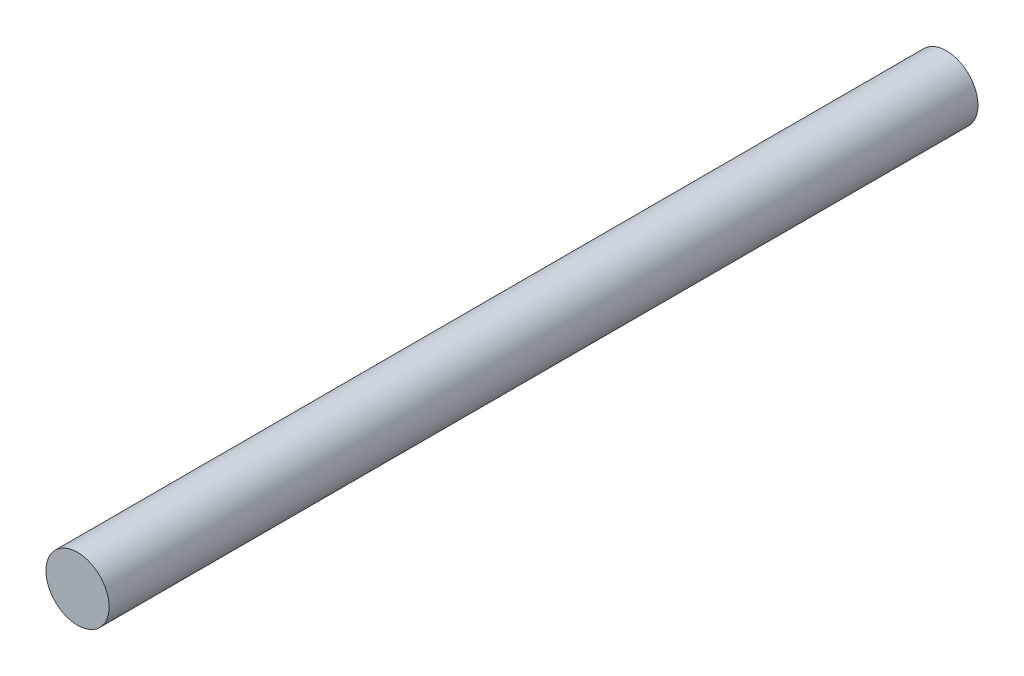
SolidWorks part; units mm, degrees
ref_plane "Plan de face" through (0, 0, 0) normal (0, 0, 1) x (1, 0, 0)
ref_plane "Plan de dessus" through (0, 0, 0) normal (0, 1, 0) x (1, 0, 0)
ref_plane "Plan de droite" through (0, 0, 0) normal (1, 0, 0) x (0, 0, -1)
sketch "Sketch1" plane through (0, 0, 0) normal (0, 0, 1) x (1, 0, 0)
  circle A0 centre (0, 0) radius 4
  dimension "D1" = 8
extrude "Boss-Extrude1" add sketch "Sketch1" along normal blind 110
